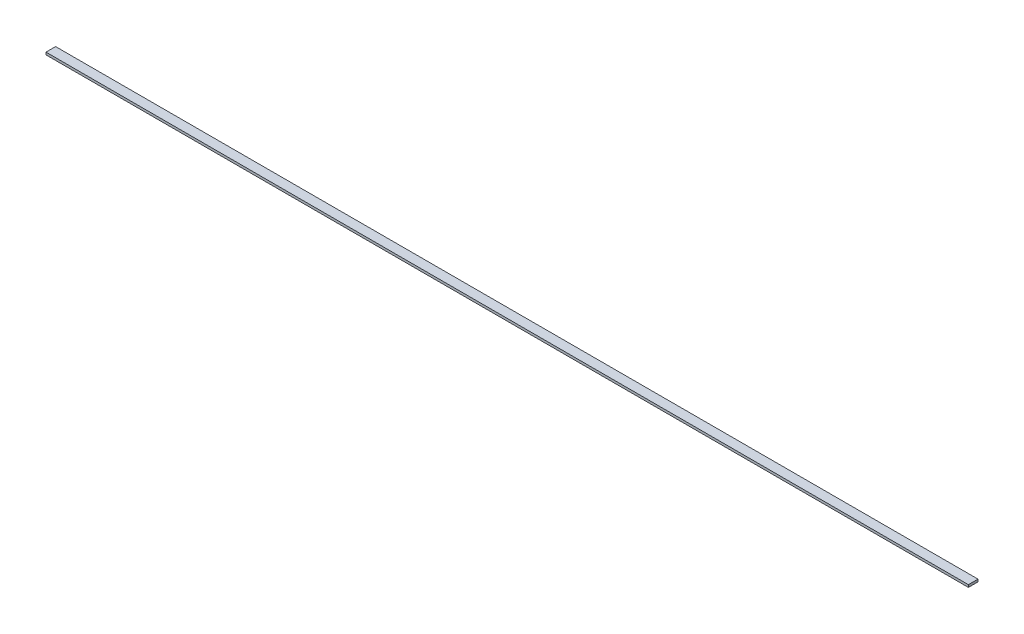
SolidWorks part; units mm, degrees
ref_plane "Front Plane" through (0, 0, 0) normal (0, 0, 1) x (1, 0, 0)
ref_plane "Top Plane" through (0, 0, 0) normal (0, 1, 0) x (1, 0, 0)
ref_plane "Right Plane" through (0, 0, 0) normal (1, 0, 0) x (0, 0, -1)
sketch "Sketch1" plane through (0, 0, 0) normal (0, 1, 0) x (1, 0, 0)
  line L1 (-1219.2, -12.7) -> (1219.2, -12.7)
  line L2 (-1219.2, -12.7) -> (-1219.2, 12.7)
  line L3 (-1219.2, 12.7) -> (1219.2, 12.7)
  line L4 (1219.2, -12.7) -> (1219.2, 12.7)
  line L5 (-1219.2, -12.7) -> (1219.2, 12.7) construction
  line L6 (-1219.2, 12.7) -> (1219.2, -12.7) construction
  point P0 (0, 0)
  dimension "D1" = 2438.4
  dimension "D2" = 25.4
extrude "Boss-Extrude1" add sketch "Sketch1" along normal blind 6.35
equation "\"horizontal-component-length\"= 96in"
equation "\"horizontal-component-width\" = 1in"
equation "\"D1@Sketch1\"=\"horizontal-component-length\""
equation "\"D2@Sketch1\"=\"horizontal-component-width\""
equation "\"material-thickness\"= .25in"
equation "\"D1@Boss-Extrude1\"=\"material-thickness\""
